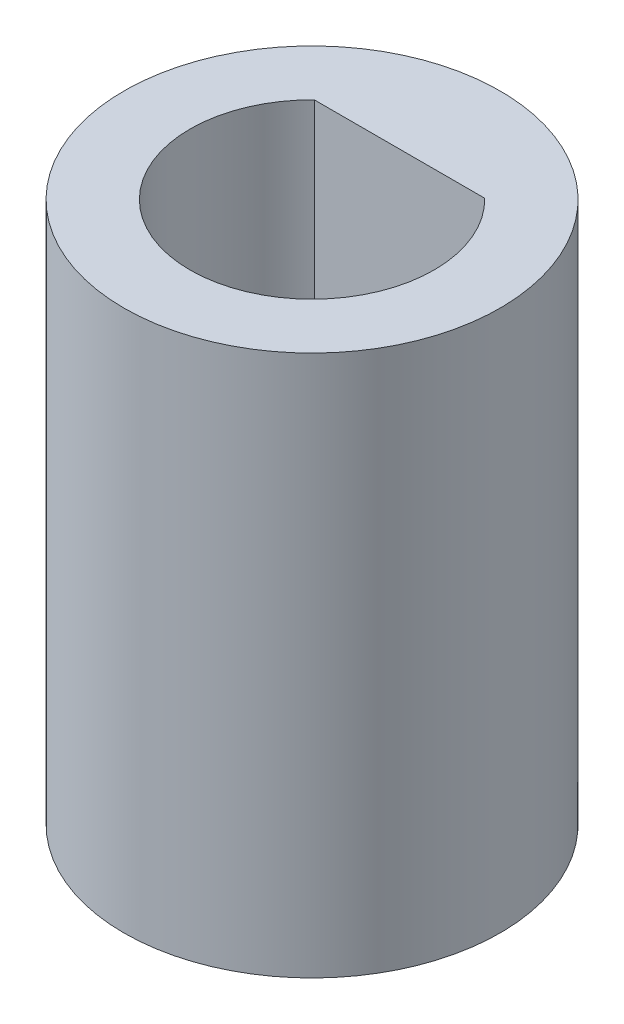
SolidWorks part; units mm, degrees
ref_plane "Front Plane" through (0, 0, 0) normal (0, 0, 1) x (1, 0, 0)
ref_plane "Top Plane" through (0, 0, 0) normal (0, 1, 0) x (1, 0, 0)
ref_plane "Right Plane" through (0, 0, 0) normal (1, 0, 0) x (0, 0, -1)
sketch "Sketch1" plane through (0, 0, 0) normal (0, 1, 0) x (1, 0, 0)
  line L0 (-2.5822, 2.65) -> (2.5822, 2.65) construction
  circle A0 centre (0, 0) radius 5.7
  circle A1 centre (0, 0) radius 3.7 construction
  arc A2 (-2.5822, 2.65) -> (2.5822, 2.65) centre (0, 0) ccw construction
  point P6 (0, -3.7)
  dimension "D1" = 7.4
  dimension "D2" = 2
  dimension "D3" = 6.35
extrude "Boss-Extrude1" add sketch "Sketch1" against normal blind 16.4
ref_plane "Plane1" through (0, 0, 0) normal (0, 1, 0) x (1, 0, 0)
sketch "Sketch3" plane through (0, 0, 0) normal (0, 1, 0) x (1, 0, 0)
  line L0 (-2.5822, 2.65) -> (2.5822, 2.65) construction
  line L1 (-2.5822, 2.65) -> (2.5822, 2.65)
  circle A0 centre (0, 0) radius 3.7 construction
  arc A1 (-2.5822, 2.65) -> (2.5822, 2.65) centre (0, 0) ccw
extrude "Cut-Extrude1" cut sketch "Sketch3" against normal through all
